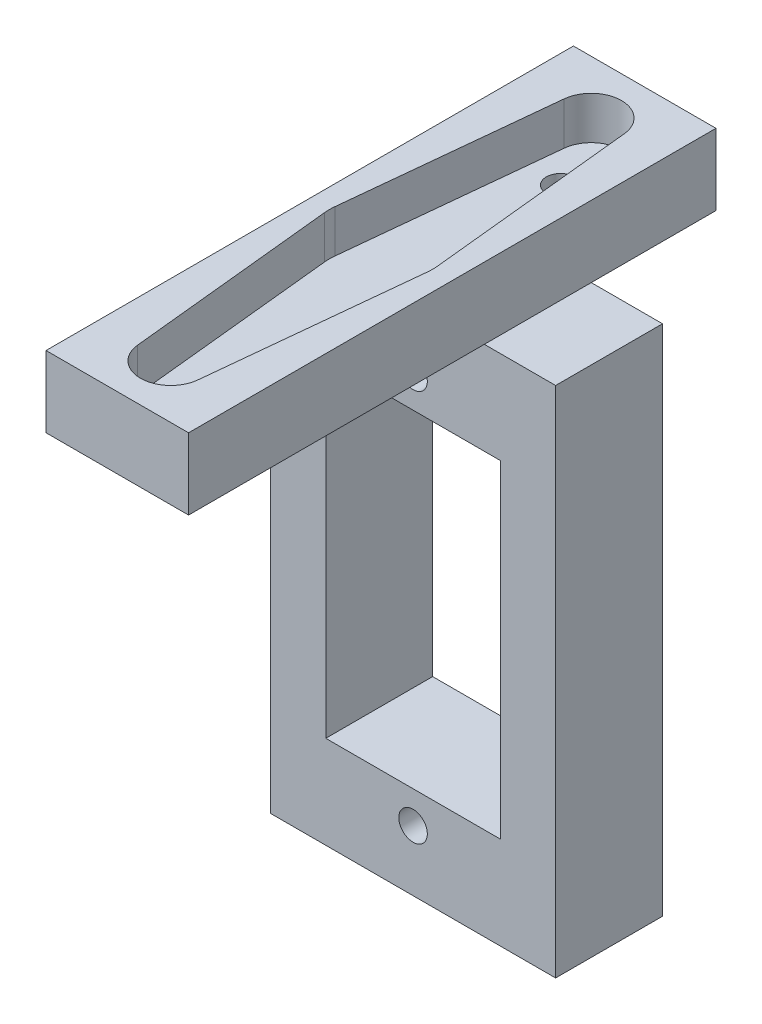
SolidWorks part; units mm, degrees
ref_plane "前视基准面" through (0, 0, 0) normal (0, 0, 1) x (1, 0, 0)
ref_plane "上视基准面" through (0, 0, 0) normal (0, 1, 0) x (1, 0, 0)
ref_plane "右视基准面" through (0, 0, 0) normal (1, 0, 0) x (0, 0, -1)
sketch "草图1" plane through (0, 0, 0) normal (0, 1, 0) x (1, 0, 0)
  line L1 (-5, 18.5) -> (5, 18.5)
  line L2 (-5, 18.5) -> (-5, -18.5)
  line L3 (-5, -18.5) -> (5, -18.5)
  line L4 (5, 18.5) -> (5, -18.5)
  line L5 (-5, 18.5) -> (5, -18.5) construction
  line L6 (-5, -18.5) -> (5, 18.5) construction
  point P0 (0, 0)
  dimension "D1" = 37
  dimension "D2" = 10
extrude "凸台-拉伸1" add sketch "草图1" against normal blind 5
sketch "草图2" plane through (0, 0, 0) normal (0, 1, 0) x (1, 0, 0)
  line L0 (-5, 0) -> (5, 0) construction
  line L1 (-5, 18.5) -> (-5, -18.5) construction
  line L2 (5, -18.5) -> (5, 18.5) construction
  line L3 (0, 18.5) -> (0, -18.5) construction
  line L4 (5, 18.5) -> (-5, 18.5) construction
  line L5 (-5, -18.5) -> (5, -18.5) construction
  line L6 (-2.114, 14.9661) -> (-3.6062, 0.3686)
  line L7 (2.114, 14.9661) -> (3.6062, 0.3686)
  line L8 (-2.114, -14.9661) -> (-3.6062, -0.3686)
  line L9 (2.114, -14.9661) -> (3.6062, -0.3686)
  arc A0 (3.6062, -0.3686) -> (3.6062, 0.3686) centre (0, 0) ccw
  arc A1 (2.114, 14.9661) -> (-2.114, 14.9661) centre (0, 14.75) ccw
  arc A2 (2.114, -14.9661) -> (-2.114, -14.9661) centre (0, -14.75) cw
  arc A3 (-3.6062, 0.3686) -> (-3.6062, -0.3686) centre (0, 0) ccw
  dimension "D1" = 7.25
  dimension "D2" = 4.25
  dimension "D3" = 14.75
extrude "切除-拉伸1" cut sketch "草图2" against normal blind 3
sketch "草图3" plane through (0, -5, 0) normal (0, -1, 0) x (1, 0, 0)
  line L0 (-5, 0) -> (5, 0) construction
  line L1 (-5, -18.5) -> (-5, 18.5) construction
  line L2 (5, 18.5) -> (5, -18.5) construction
  line L3 (0, 18.5) -> (0, -18.5) construction
  line L4 (-5, 18.5) -> (5, 18.5) construction
  line L5 (5, -18.5) -> (-5, -18.5) construction
  line L6 (-5, -6) -> (5, -6) construction
  line L8 (-10, -2.25) -> (10, -2.25)
  line L9 (-10, -2.25) -> (-10, -9.75)
  line L10 (-10, -9.75) -> (10, -9.75)
  line L11 (10, -2.25) -> (10, -9.75)
  line L12 (-10, -2.25) -> (10, -9.75) construction
  line L13 (-10, -9.75) -> (10, -2.25) construction
  point P14 (0, -6)
  dimension "D1" = 6
  dimension "D2" = 20
  dimension "D3" = 7.5
extrude "凸台-拉伸2" add sketch "草图3" along normal blind 36
sketch "草图6" plane through (0, 0, -2.25) normal (0, 0, 1) x (1, 0, 0)
  line L0 (-10, -23) -> (10, -23) construction
  line L1 (-10, -41) -> (-10, -5) construction
  line L2 (10, -41) -> (10, -5) construction
  line L3 (0, -41) -> (0, -5) construction
  line L4 (10, -41) -> (-10, -41) construction
  line L5 (5, -5) -> (-5, -5) construction
  line L7 (-6.125, -11.5) -> (6.125, -11.5)
  line L8 (-6.125, -11.5) -> (-6.125, -34.5)
  line L9 (-6.125, -34.5) -> (6.125, -34.5)
  line L10 (6.125, -11.5) -> (6.125, -34.5)
  line L11 (-6.125, -11.5) -> (6.125, -34.5) construction
  line L12 (-6.125, -34.5) -> (6.125, -11.5) construction
  point P12 (0, -23)
  dimension "D1" = 23
  dimension "D2" = 12.25
extrude "切除-拉伸2" cut sketch "草图6" against normal through all
sketch "草图7" plane through (0, -3, 0) normal (0, 1, 0) x (1, 0, 0)
  line L0 (3.625, 0) -> (-3.625, 0) construction
  line L1 (0, 16.875) -> (0, -16.875) construction
  arc A0 (3.6062, -0.3686) -> (3.6062, 0.3686) centre (0, 0) ccw construction
  arc A1 (-3.6062, 0.3686) -> (-3.6062, -0.3686) centre (0, 0) ccw construction
  arc A2 (2.114, 14.9661) -> (-2.114, 14.9661) centre (0, 14.75) ccw construction
  arc A3 (-2.114, -14.9661) -> (2.114, -14.9661) centre (0, -14.75) ccw construction
  circle A4 centre (0, 12.6) radius 1
  circle A5 centre (0, -12.6) radius 1
  dimension "D1" = 12.6
  dimension "D2" = 2
extrude "切除-拉伸3" cut sketch "草图7" against normal up to next
sketch "草图9" plane through (0, 0, -9.75) normal (0, 0, -1) x (-1, 0, 0)
  line L0 (-10, -23) -> (10, -23) construction
  line L1 (-10, -41) -> (-10, -5) construction
  line L2 (10, -41) -> (10, -5) construction
  line L3 (0, -5) -> (0, -41) construction
  line L4 (5, -5) -> (-5, -5) construction
  line L5 (10, -41) -> (-10, -41) construction
  circle A0 centre (0, -9.25) radius 1
  circle A1 centre (0, -36.75) radius 1
  dimension "D1" = 2
  dimension "D2" = 27.5
extrude "切除-拉伸4" cut sketch "草图9" against normal up to next
